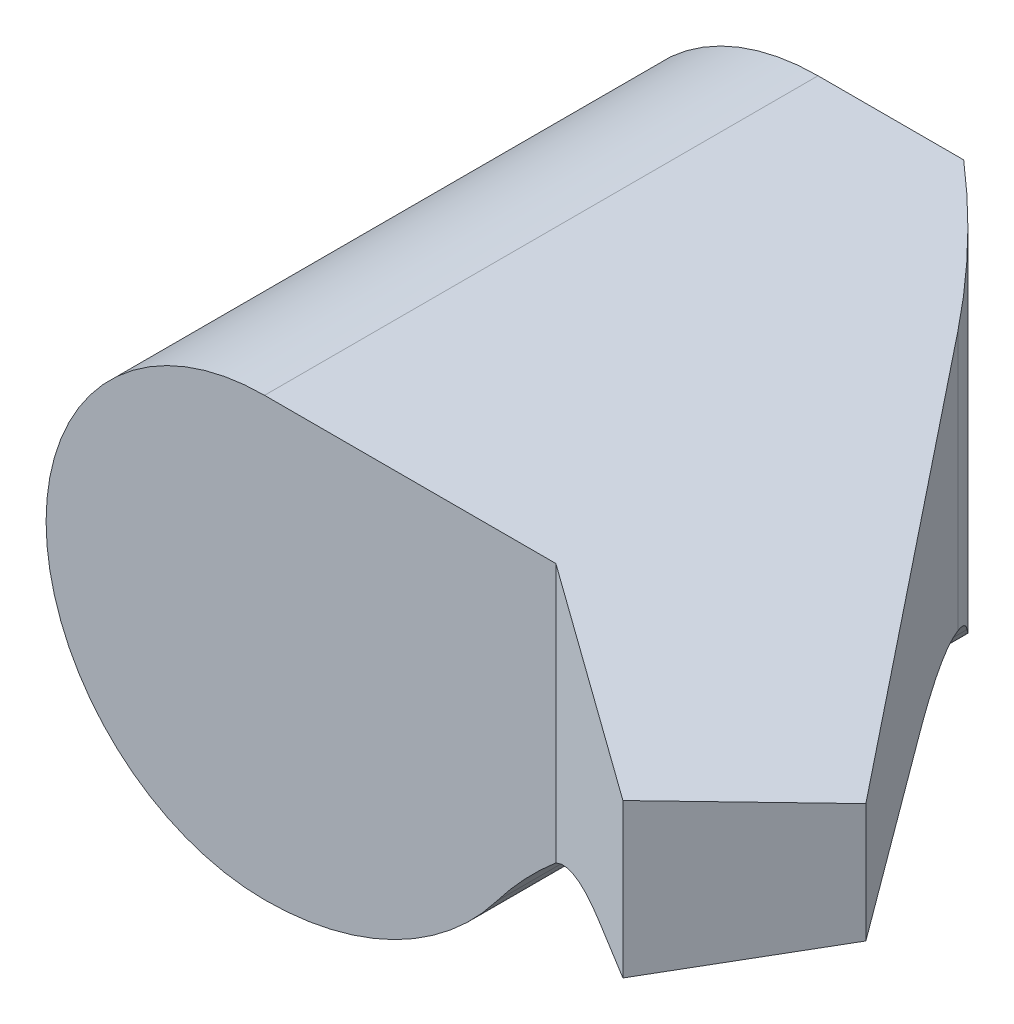
SolidWorks part; units mm, degrees
ref_plane "Front Plane" through (0, 0, 0) normal (0, 0, 1) x (1, 0, 0)
ref_plane "Top Plane" through (0, 0, 0) normal (0, 1, 0) x (1, 0, 0)
ref_plane "Right Plane" through (0, 0, 0) normal (1, 0, 0) x (0, 0, -1)
sketch "Sketch1" plane through (0, 0, 0) normal (0, 0, 1) x (1, 0, 0)
  line L0 (-16.0247, 26.6737) -> (3.9753, 26.6737)
  line L1 (3.9753, 26.6737) -> (3.9753, -3.3263)
  line L2 (3.9753, -3.3263) -> (-16.0247, -3.3263)
  arc A0 (-16.0247, 26.6737) -> (-16.0247, -3.3263) centre (-16.0247, 11.6737) ccw
  point P5 (-1.531, 2.3116)
  point P6 (0, -0.523)
  point P7 (2.5314, -1.3263)
  dimension "D1" = 15
  dimension "D2" = 30
  dimension "D3" = 20
extrude "Boss-Extrude1" add sketch "Sketch1" along normal blind 38
sketch "Sketch2" plane through (0, -3.3263, 0) normal (0, -1, 0) x (1, 0, 0)
  line L0 (3.9753, 38) -> (3.9753, 10.4027)
  line L1 (-16.0247, 38) -> (3.9753, 38) construction
  line L2 (3.9753, 38) -> (3.9753, 0) construction
  line L4 (28.8946, 41.635) -> (20.3704, 49.7919)
  line L5 (20.3704, 49.7919) -> (3.9753, 38)
  line L6 (3.9753, 10.4027) -> (28.8946, 41.635)
  point P6 (3.9753, 38)
  point P9 (30.3511, 44.7309)
  point P10 (20.3704, 49.7919)
  point P11 (3.9753, 10.4027)
  point P12 (28.8946, 41.635)
extrude "Boss-Extrude3" add sketch "Sketch2" against normal blind 30
sketch "Sketch4" plane through (0, -3.3263, 0) normal (0, -1, 0) x (1, 0, 0)
  line L0 (-16.0247, 0) -> (3.9753, 0) construction
  line L1 (3.9753, 10.4027) -> (28.8946, 41.635) construction
  line L2 (-6.0247, 0) -> (8.5864, -30.7506)
  line L3 (8.5864, -30.7506) -> (53.6395, 0)
  line L4 (53.6395, 0) -> (3.9753, 10.4027)
  arc A0 (3.9753, 10.4027) -> (-6.0247, 0) centre (-57.2627, 59.2625) cw
extrude "Cut-Extrude2" cut sketch "Sketch4" against normal blind 61
sketch "Sketch3" plane through (0, 0, 0) normal (0, 0, -1) x (-1, 0, 0)
  line L0 (-14.4712, 14.4711) -> (-28.8946, 18.5065)
  line L1 (-28.8946, 26.6737) -> (-28.8946, -3.3263) construction
  line L2 (16.0247, -3.3263) -> (-3.3013, -44.7183)
  line L3 (-3.3013, -44.7183) -> (-57.4216, 26.7258)
  line L4 (-57.4216, 26.7258) -> (-28.8946, 18.5065)
  line L5 (16.0247, -3.3263) -> (6.0247, -3.3263) construction
  arc A1 (16.0247, -3.3263) -> (16.0247, 26.6737) centre (16.0247, 11.6737) ccw construction
  arc A3 (16.0247, -3.3263) -> (0.0728, 4.587) centre (16.0247, 16.7086) cw
  arc A4 (0.0728, 4.587) -> (-14.4712, 14.4711) centre (-21.9103, -12.1176) ccw
  point P2 (1.5625, 5.4279)
  point P17 (-1.7604, 7.4842)
  point P18 (-28.8946, 18.5065)
  point P19 (-14.4712, 14.4711)
extrude "Cut-Extrude1" cut sketch "Sketch3" against normal blind 61
